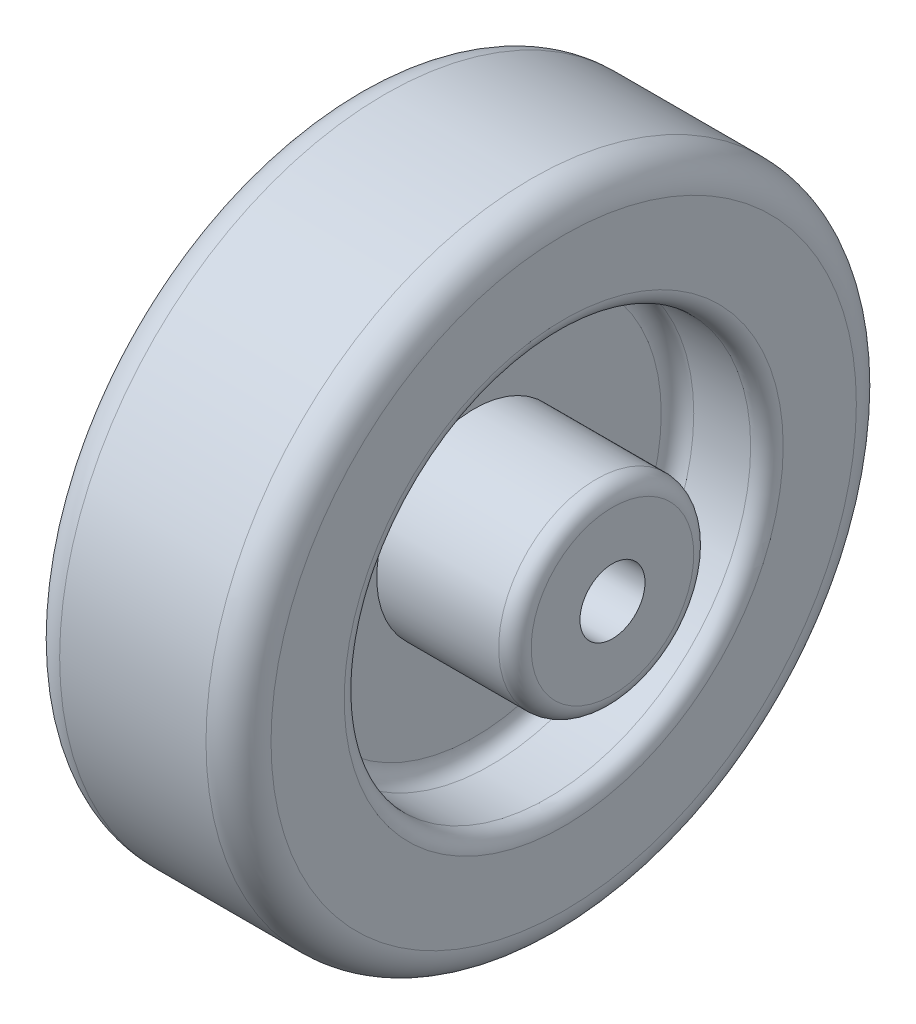
SolidWorks part; units mm, degrees
ref_plane "Front Plane" through (0, 0, 0) normal (0, 0, 1) x (1, 0, 0)
ref_plane "Top Plane" through (0, 0, 0) normal (0, 1, 0) x (1, 0, 0)
ref_plane "Right Plane" through (0, 0, 0) normal (1, 0, 0) x (0, 0, -1)
sketch "Sketch1" plane through (0, 0, 0) normal (1, 0, 0) x (0, 0, -1)
  circle A0 centre (0, 0) radius 40
extrude "Boss-Extrude1" add sketch "Sketch1" along normal blind 13
sketch "Sketch2" plane through (13, 0, 0) normal (1, 0, 0) x (0, 0, -1)
  circle A0 centre (0, 0) radius 25
extrude "Cut-Extrude1" cut sketch "Sketch2" against normal blind 11
sketch "Sketch3" plane through (2, 0, 0) normal (1, 0, 0) x (0, 0, -1)
  circle A0 centre (0, 0) radius 12
extrude "Boss-Extrude2" add sketch "Sketch3" along normal blind 17
sketch "Sketch4" plane through (19, 0, 0) normal (1, 0, 0) x (0, 0, -1)
  circle A0 centre (0, 0) radius 4
extrude "Cut-Extrude2" cut sketch "Sketch4" against normal through all
fillet "Fillet1" radius 2 3 edges at (2, 0, -25) (13, 0, -25) (19, 0, -12)
fillet "Fillet2" radius 4 1 edges at (13, 0, -40)
mirror "Mirror2" about plane through (0, 0, 0) normal (1, 0, 0) of "Cut-Extrude1", "Cut-Extrude2", "Fillet1", "Boss-Extrude2", "Boss-Extrude1", "Fillet2"
